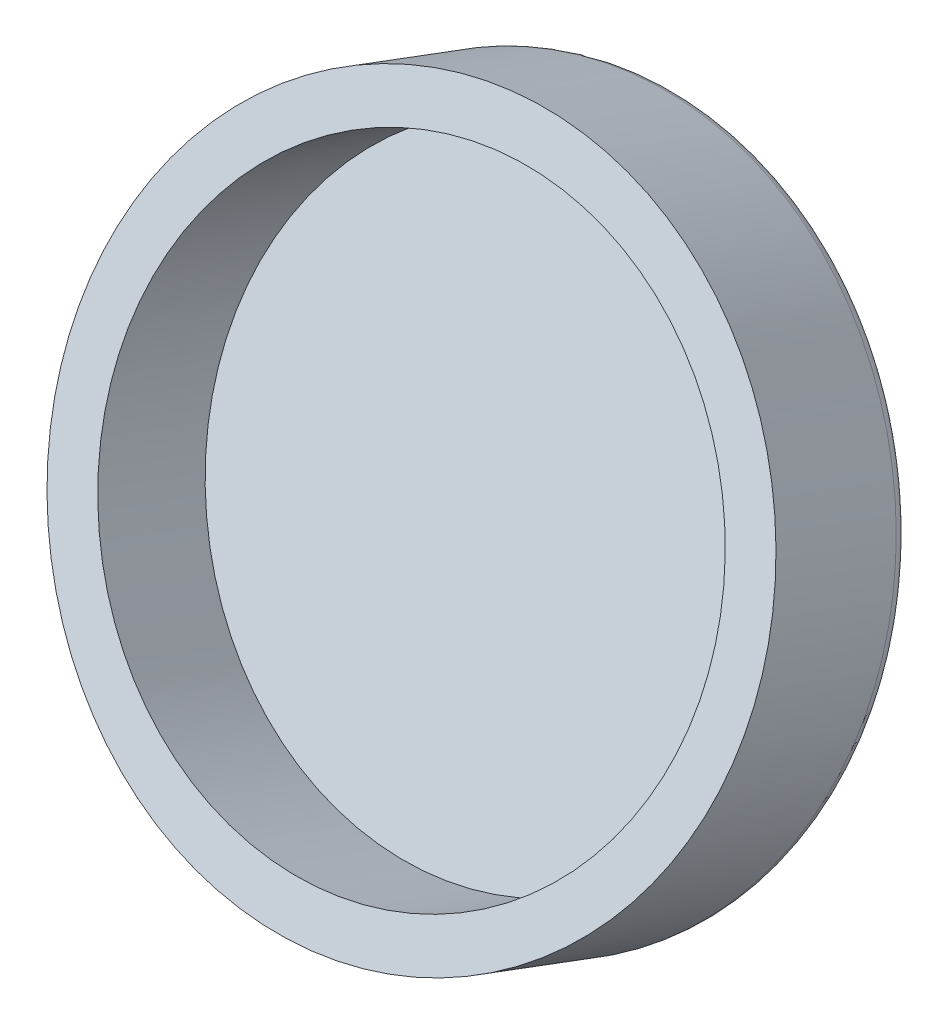
SolidWorks part; units mm, degrees
ref_plane "Plan de face" through (0, 0, 0) normal (0, 0, 1) x (1, 0, 0)
ref_plane "Plan de dessus" through (0, 0, 0) normal (0, 1, 0) x (1, 0, 0)
ref_plane "Plan de droite" through (0, 0, 0) normal (1, 0, 0) x (0, 0, -1)
ref_plane "Plan1" through (0, -1.4222, 0.591) normal (0, -0.9234, 0.3838) x (1, 0, 0)
sketch "Esquisse1" plane through (0, -1.4222, 0.591) normal (0, -0.9234, 0.3838) x (1, 0, 0)
  line L0 (-3.5511, 74.9194) -> (-20.5184, 75.9737)
  line L1 (-20.5184, 75.9737) -> (-20.6362, 74.0774)
  line L2 (-20.6362, 74.0774) -> (-2.0705, 72.9237)
  line L3 (-0.8629, 73.8395) -> (-0.3351, 82.3342)
  line L4 (-0.3351, 82.3342) -> (-3.0798, 82.5047)
  line L5 (-3.0798, 82.5047) -> (-3.5511, 74.9194)
  line L6 (-20.0355, 83.7444) -> (-20.7087, 72.9105) construction
  arc A0 (-2.0705, 72.9237) -> (-0.8629, 73.8395) centre (-1.861, 73.9015) ccw
  dimension "D1" = 9.5
  dimension "D2" = 19.75
  dimension "D3" = 7.6
  dimension "D4" = 34
revolve "Révolution1" add sketch "Esquisse1" angle 360 about L6
